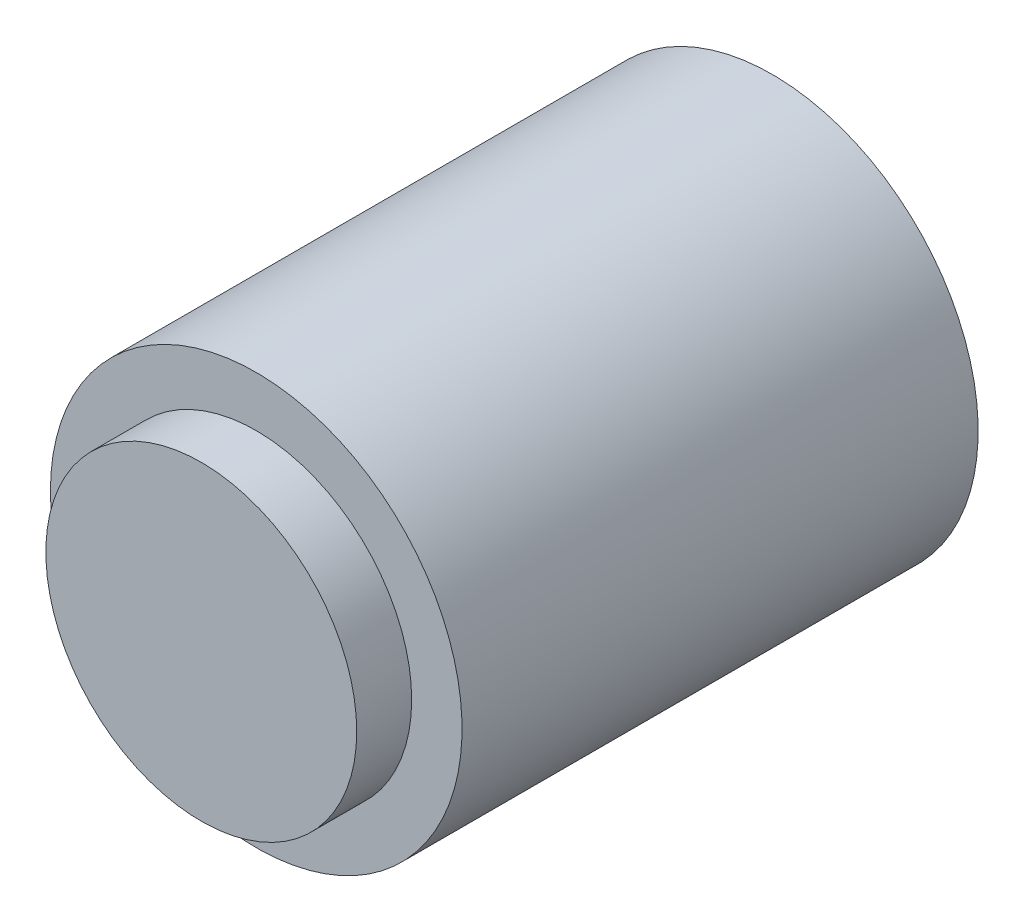
SolidWorks part; units mm, degrees
material "Rubber"
ref_plane "Front Plane" through (0, 0, 0) normal (0, 0, 1) x (1, 0, 0)
ref_plane "Top Plane" through (0, 0, 0) normal (0, 1, 0) x (1, 0, 0)
ref_plane "Right Plane" through (0, 0, 0) normal (1, 0, 0) x (0, 0, -1)
sketch "Sketch1" plane through (0, 0, 0) normal (0, 0, 1) x (1, 0, 0)
  circle A0 centre (0, 0) radius 16.75
  dimension "D1" = 33.5
extrude "Boss-Extrude1" add sketch "Sketch1" along normal blind 42
sketch "Sketch2" plane through (0, 0, 42) normal (0, 0, 1) x (1, 0, 0)
  circle A0 centre (0, 0) radius 12.65
  dimension "D1" = 25.3
extrude "Boss-Extrude2" add sketch "Sketch2" along normal blind 4.47
sketch "Sketch3" plane through (0, 0, 0) normal (0, 0, -1) x (-1, 0, 0)
  circle A0 centre (0, 0) radius 15.5
  dimension "D1" = 31
extrude "Cut-Extrude1" cut sketch "Sketch3" against normal blind 4.7
